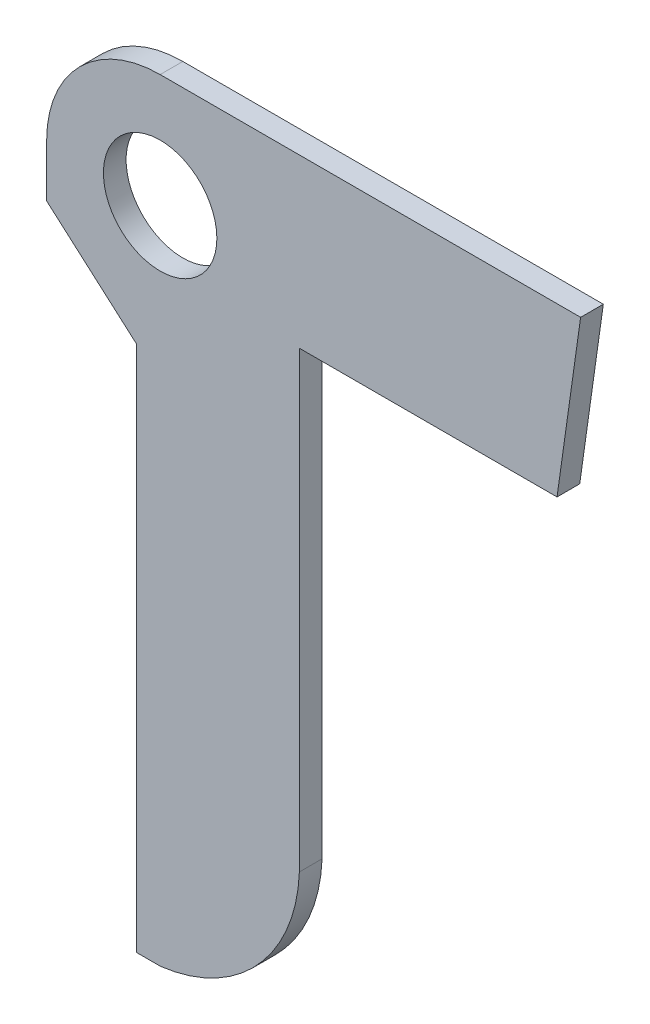
SolidWorks part; units mm, degrees
ref_plane "정면" through (0, 0, 0) normal (0, 0, 1) x (1, 0, 0)
ref_plane "윗면" through (0, 0, 0) normal (0, 1, 0) x (1, 0, 0)
ref_plane "우측면" through (0, 0, 0) normal (1, 0, 0) x (0, 0, -1)
sketch "스케치1" plane through (0, 0, 0) normal (0, 0, 1) x (1, 0, 0)
  line L0 (-5, 0) -> (-5, -2.3265)
  line L1 (-1.0436, -29.0249) -> (0.0233, -29.0249)
  line L2 (6.1347, -22.3632) -> (6.1347, -2.3761)
  line L3 (6.1347, -2.3761) -> (17.4895, -2.3761)
  line L4 (17.4895, -2.3761) -> (18.529, 5)
  line L5 (18.529, 5) -> (0, 5)
  line L6 (-5, -2.3265) -> (-1.0436, -5.7996)
  line L7 (-1.0436, -5.7996) -> (-1.0436, -29.0249)
  circle A0 centre (0, 0) radius 2.5
  circle A1 centre (0, 0) radius 5
  arc A2 (0.0233, -29.0249) -> (6.1347, -22.3632) centre (-0.8368, -22.1017) ccw
  dimension "D1" = 5
  dimension "D2" = 10
extrude "보스-돌출1" add sketch "스케치1" along normal blind 1 contours A1 L0 L1 L2 L3 L4 L5 | A1 A0
